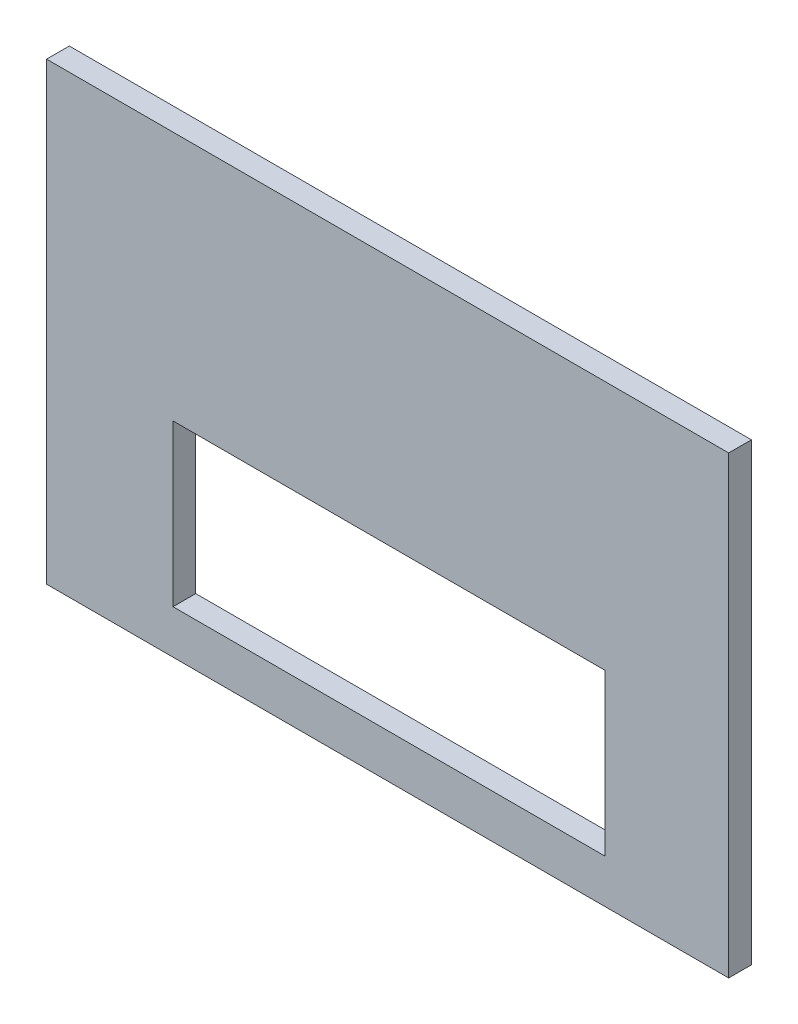
SolidWorks part; units mm, degrees
ref_plane "Front Plane" through (0, 0, 0) normal (0, 0, 1) x (1, 0, 0)
ref_plane "Top Plane" through (0, 0, 0) normal (0, 1, 0) x (1, 0, 0)
ref_plane "Right Plane" through (0, 0, 0) normal (1, 0, 0) x (0, 0, -1)
sketch "Sketch1" plane through (0, 0, 0) normal (0, 0, 1) x (1, 0, 0)
  line L1 (-15.3846, 95.1923) -> (284.6154, 95.1923)
  line L2 (-15.3846, 95.1923) -> (-15.3846, -104.8077)
  line L3 (-15.3846, -104.8077) -> (284.6154, -104.8077)
  line L4 (284.6154, 95.1923) -> (284.6154, -104.8077)
  line L6 (40.2197, -14.8077) -> (230.2946, -14.8077)
  line L7 (40.2197, -14.8077) -> (40.2197, -85.5852)
  line L8 (40.2197, -85.5852) -> (230.2946, -85.5852)
  line L9 (230.2946, -14.8077) -> (230.2946, -85.5852)
  dimension "D1" = 300
  dimension "D2" = 200
extrude "Boss-Extrude1" add sketch "Sketch1" along normal blind 10
